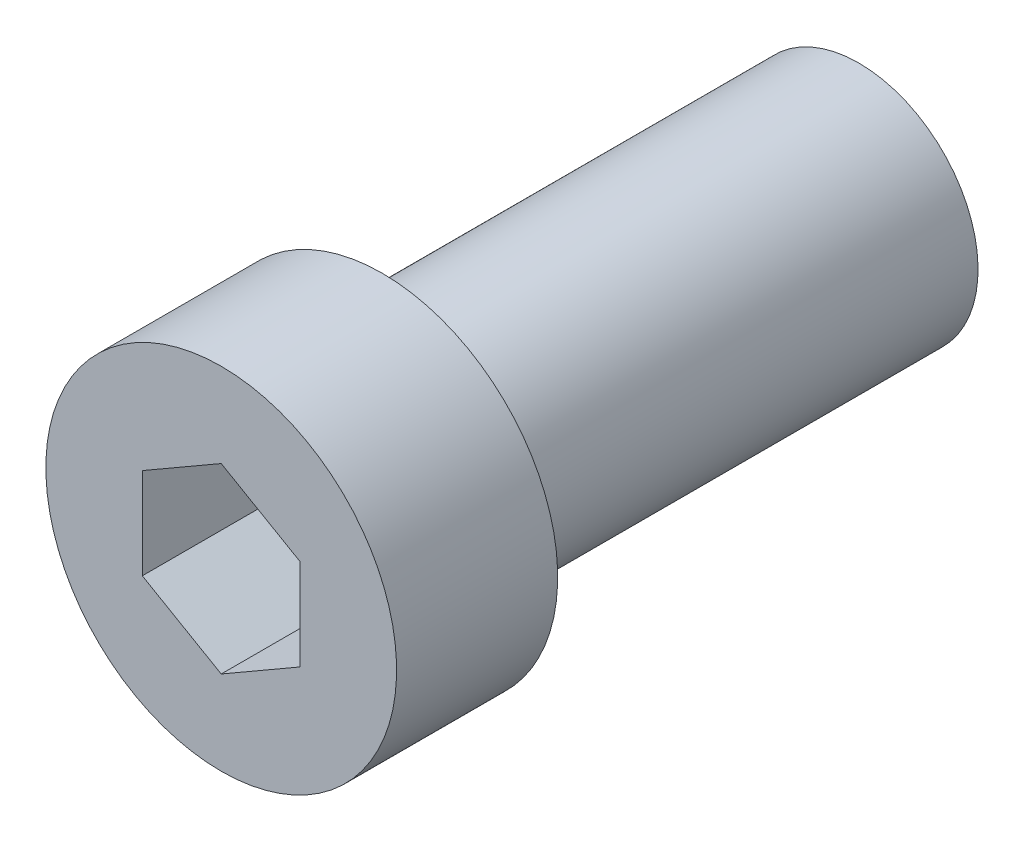
SolidWorks part; units mm, degrees
ref_plane "前视基准面" through (0, 0, 0) normal (0, 0, 1) x (1, 0, 0)
ref_plane "上视基准面" through (0, 0, 0) normal (0, 1, 0) x (1, 0, 0)
ref_plane "右视基准面" through (0, 0, 0) normal (1, 0, 0) x (0, 0, -1)
ref_plane "基准面1" through (0, 0, 0) normal (0, -1, 0) x (1, 0, 0)
sketch "草图1" plane through (0, 0, 0) normal (0, -1, 0) x (1, 0, 0)
  line L0 (2.208, 2.028) -> (0, 2.028)
  line L1 (0, 2.028) -> (0, 0)
  line L2 (0, 0) -> (2.208, 0)
  line L3 (2.208, 0) -> (2.208, 2.028)
  line L4 (0, 2.028) -> (0, 0) construction
revolve "旋转1" add sketch "草图1" angle 360 about L4
sketch "草图2" plane through (0, 0, 0) normal (0, 0, -1) x (-1, 0, 0)
  circle A0 centre (0, 0) radius 1.5
extrude "凸台-拉伸1" add sketch "草图2" along normal blind 6
sketch "草图3" plane through (0, 0, 2.028) normal (0, 0, 1) x (1, 0, 0)
  line L0 (0.9936, -0.5737) -> (0.9936, 0.5737)
  line L1 (0.9936, 0.5737) -> (0, 1.1473)
  line L2 (0, 1.1473) -> (-0.9936, 0.5737)
  line L3 (-0.9936, 0.5737) -> (-0.9936, -0.5737)
  line L4 (-0.9936, -0.5737) -> (0, -1.1473)
  line L5 (0, -1.1473) -> (0.9936, -0.5737)
extrude "切除-拉伸1" cut sketch "草图3" against normal blind 1.872
